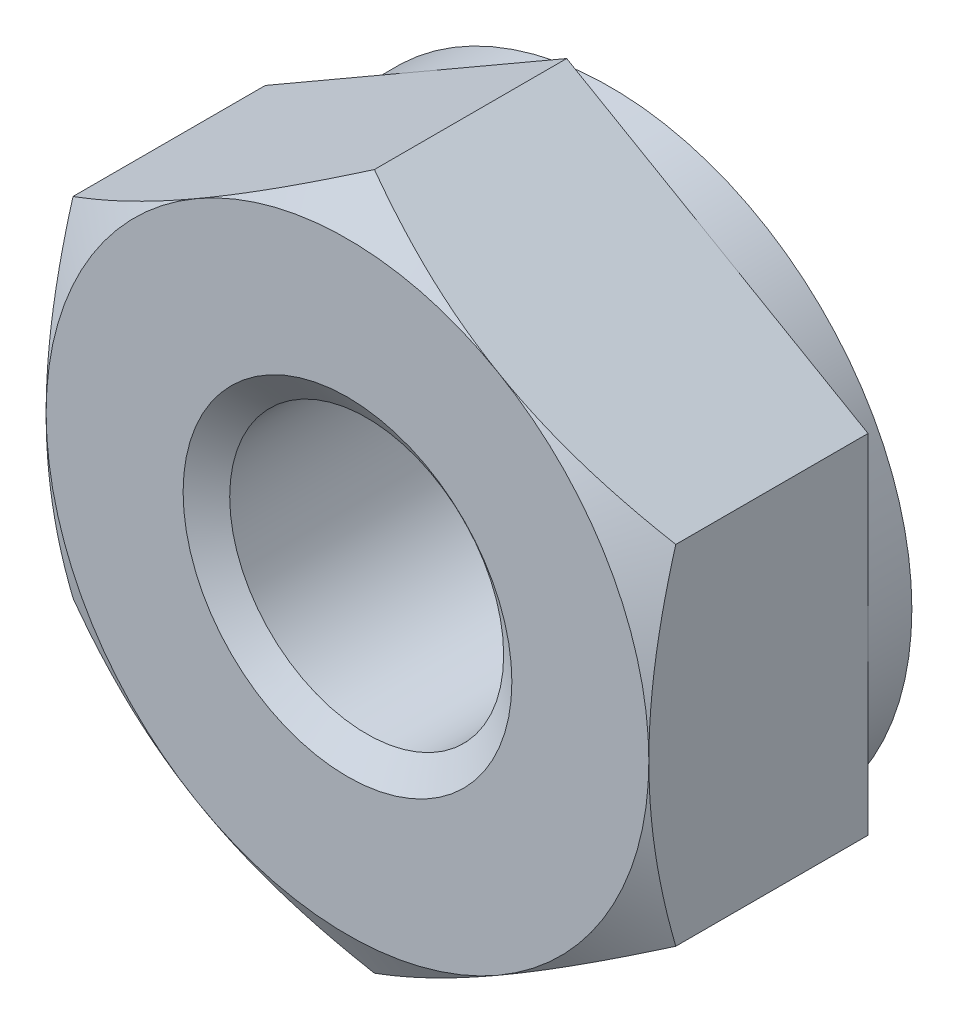
SolidWorks part; units mm, degrees
ref_plane "Plane1" through (0, 0, 0) normal (0, 0, 1) x (1, 0, 0)
ref_plane "Plane2" through (0, 0, 0) normal (0, 1, 0) x (1, 0, 0)
ref_plane "Plane3" through (0, 0, 0) normal (1, 0, 0) x (0, 0, -1)
sketch "BaseNutSke" plane through (0, 0, 0) normal (0, 0, 1) x (1, 0, 0)
  line L6 (2.75, 1.5877) -> (2.75, -1.5877)
  line L7 (-2.75, 1.5877) -> (-2.75, -1.5877)
  line L8 (2.75, 1.5877) -> (0, 3.1754)
  line L9 (0, 3.1754) -> (-2.75, 1.5877)
  line L10 (-2.75, -1.5877) -> (0, -3.1754)
  line L11 (0, -3.1754) -> (2.75, -1.5877)
  circle A0 centre (0, 0) radius 1.25
extrude "BaseNut" add sketch "BaseNutSke" against normal blind 2.4
cosmetic thread "ThreadCosmetic" [suppressed] parameters "Thread_major"=3
sketch "Sketch4" plane through (0, 0, 0) normal (1, 0, 0) x (0, 0, -1)
  line L0 (2.4, 2.75) -> (2, 2.75)
  line L1 (2.4, 2.75) -> (2.4, 13.1754)
  line L2 (2, 13.1754) -> (2.4, 13.1754)
  line L3 (2, 13.1754) -> (2, 2.75)
  line L4 (0, 0) -> (34.925, 0) construction
  line L6 (2.4, 1.5877) -> (2.4, 3.1754) construction
  line L7 (0, 2.75) -> (-10, 2.75)
  line L8 (0, 1.5877) -> (0, 3.1754) construction
  line L9 (0.2456, 3.1754) -> (0.2456, 13.1754)
  line L10 (0.2456, 13.1754) -> (-10, 13.1754)
  line L11 (-10, 13.1754) -> (-10, 2.75)
  line L12 (0, 2.75) -> (0.2456, 3.1754)
  line L14 (0, 1.5877) -> (0, -1.5877) construction
  line L15 (2.4, 3.1754) -> (0, 3.1754) construction
revolve "Bearing-Face" cut sketch "Sketch4" angle 360 about L4
sketch "Sketch3" plane through (0, 0, 0) normal (1, 0, 0) x (0, 0, -1)
  line L0 (2.4, 2.75) -> (2.1544, 3.1754)
  line L1 (2.1544, 3.1754) -> (2.1544, 13.1754)
  line L2 (2.1544, 13.1754) -> (12.4, 13.1754)
  line L3 (12.4, 13.1754) -> (12.4, 2.75)
  line L4 (12.4, 2.75) -> (2.4, 2.75)
  line L5 (2.4, 1.5877) -> (2.4, 3.1754) construction
  line L6 (2, 3.1754) -> (0.2456, 3.1754) construction
  line L7 (0, 0) -> (38.6776, 0) construction
  line L8 (2.4, 0) -> (0, 0) construction
  line L9 (1.1228, 3.1754) -> (1.1228, 44.222) construction
  line L10 (0.0912, 13.1754) -> (-10.1544, 13.1754)
  line L11 (-10.1544, 13.1754) -> (-10.1544, 2.75)
  line L12 (-10.1544, 2.75) -> (-0.1544, 2.75)
  line L13 (-0.1544, 2.75) -> (0.0912, 3.1754)
  line L14 (0.0912, 3.1754) -> (0.0912, 13.1754)
  line L16 (2, 3.1754) -> (0.2456, 3.1754) construction
revolve "Double-Chamfer" [suppressed] cut sketch "Sketch3" angle 360 about L7
sketch "Sketch5" plane through (0, 0, 0) normal (1, 0, 0) x (0, 0, -1)
  line L0 (2.3746, 1.5) -> (2.182, 1.225)
  line L1 (2.4254, 1.5) -> (2.3746, 1.5)
  line L2 (2.4254, 1.5) -> (2.4254, 1.225)
  line L3 (2.4254, 1.225) -> (2.182, 1.225)
  line L6 (-0.0508, 1.5) -> (0, 1.5)
  line L7 (0, 1.5) -> (0.1926, 1.225)
  line L9 (0.1926, 1.225) -> (-0.0508, 1.225)
  line L10 (-0.0508, 1.225) -> (-0.0508, 1.5)
  line L11 (25.0375, 0) -> (38.388, 0) construction
  line L12 (2.4, 0) -> (0, 0) construction
revolve "EndChamfer" cut sketch "Sketch5" angle 360 about L11
sketch "ThdSchSke" plane through (0, 0, 0) normal (0, 1, 0) x (1, 0, 0)
  line L0 (-1.5, 0.0254) -> (-1.25, 0.2005)
  line L1 (-1.25, 0.2005) -> (-0.625, 0.2005)
  line L2 (-0.625, 0.2005) -> (-0.625, -0.1497)
  line L3 (-0.625, -0.1497) -> (-1.25, -0.1497)
  line L4 (-1.25, -0.1497) -> (-1.5, 0.0254)
  line L5 (-3.175, 0.5) -> (3.175, 0.5) construction
  line L6 (0, 0.5) -> (0, -2.9874) construction
  line L7 (0, 2.1995) -> (0, 0.1751) construction
revolve "ThreadSchematic" [suppressed] cut sketch "ThdSchSke" angle 360 about L6
pattern_linear "ThdSchPat" [suppressed]
equation "\"D2@BaseNutSke\" = \"Width_flats@BaseNutSke\" / 2"
equation "\"D3@BaseNutSke\" = \"Width_flats@BaseNutSke\" / 2"
equation "\"D1@Sketch3\" = \"Width_flats@BaseNutSke\" /2"
equation "\"D1@Sketch4\" = \"D2@BaseNutSke\""
equation "\"D4@BaseNutSke\" = \"D3@BaseNutSke\""
equation "\"Thread_major@ThdSchSke\" = \"Thread_major@ThreadCosmetic\""
equation "\"Tap_Drill@ThdSchSke\" = \"Tap_drill@BaseNutSke\""
equation "\"OverCut@ThdSchSke\" = \"Tap_Drill@ThdSchSke\" * 0.5"
equation "\"Num_threads@ThdSchPat\" = int(  ( \"Thickness@BaseNut\" - 0.0508 ) / \"Advance@ThdSchSke\" + 0.999 )  + 1"
equation "\"Advance@ThdSchPat\" = ( \"Thickness@BaseNut\" - 0.0508 ) /  (\"Num_threads@ThdSchPat\" - 1) 'relax it"
equation "' \"Num_threads@ThdSchPat\" = \"Num_threads@ThdSchPat\" - sgn( \"Num_threads@ThdSchPat\" - 1) '---chamfered tips only---"
equation "\"ThreadMajor@Sketch5\" = \"Thread_major@ThreadCosmetic\" * 0.5"
equation "\"ChamferDepth@Sketch5\" = (\"Thread_major@ThreadCosmetic\" - \"Tap_drill@BaseNutSke\") * 0.55"
equation "\"Offset1@Sketch5\" = \"Thickness@BaseNut\" + 0.0254"
equation "\"Offset2@Sketch5\" = \"Offset1@Sketch5\" + 0.0508"
